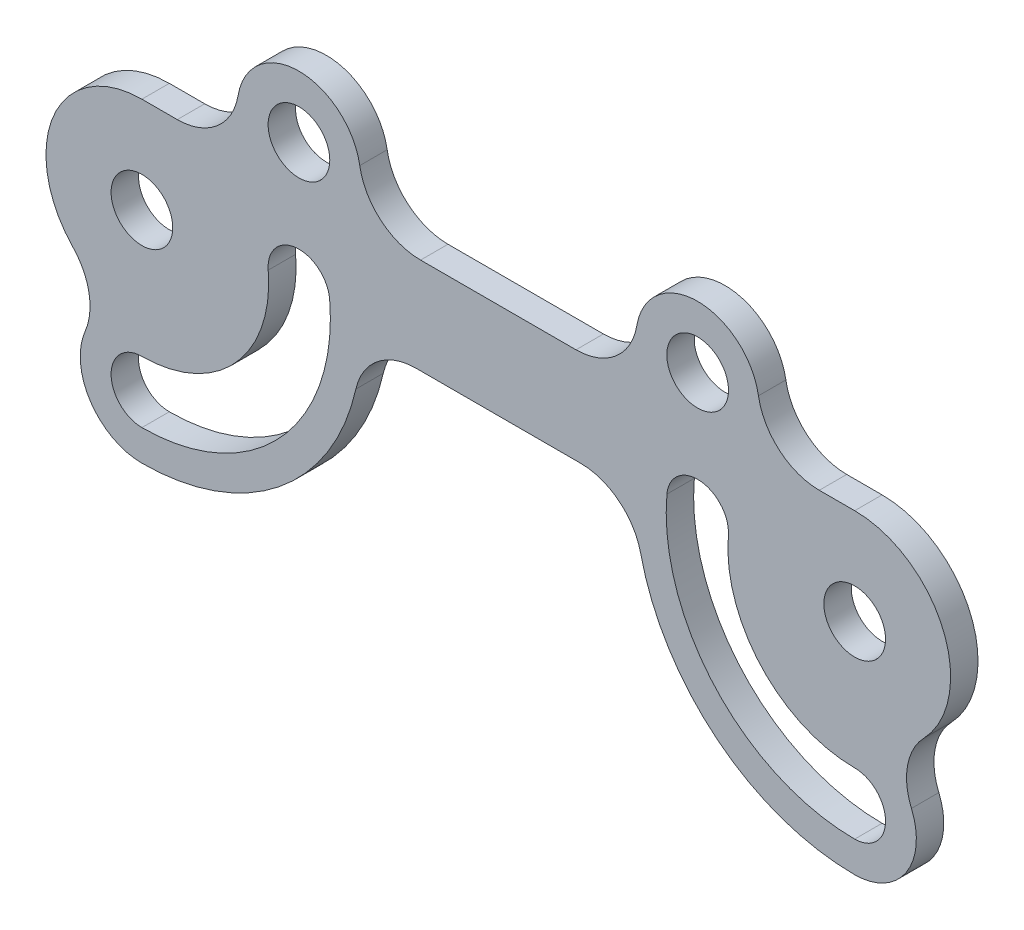
SolidWorks part; units mm, degrees
ref_plane "Front Plane" through (0, 0, 0) normal (0, 0, 1) x (1, 0, 0)
ref_plane "Top Plane" through (0, 0, 0) normal (0, 1, 0) x (1, 0, 0)
ref_plane "Right Plane" through (0, 0, 0) normal (1, 0, 0) x (0, 0, -1)
sketch "Sketch1" plane through (0, 0, 0) normal (0, 0, 1) x (1, 0, 0)
  line L0 (5.5562, 0) -> (35.7188, 0)
  line L1 (0, 5.5562) -> (41.275, 5.5562)
  line L2 (0, 5.5562) -> (0, -5.5562) construction
  line L3 (0, -5.5562) -> (41.275, -5.5562) construction
  line L4 (41.275, 5.5562) -> (41.275, -5.5562) construction
  line L5 (0, 5.5562) -> (41.275, 5.5562) construction
  line L9 (0, 0) -> (9.0934, 0.7956) construction
  line L10 (41.275, 9.1281) -> (41.275, 0) construction
  line L11 (32.1816, 0.7956) -> (30.4025, 0.9512) construction
  line L12 (32.1816, 0.7956) -> (41.275, 0) construction
  line L13 (30.4025, 0.9512) -> (28.6233, 1.1069) construction
  circle A0 centre (0, 0) radius 5.5562 construction
  circle A1 centre (41.275, 0) radius 5.5562 construction
  arc A2 (0, 5.5562) -> (0, -5.5562) centre (0, 0) ccw
  arc A3 (41.275, -5.5562) -> (41.275, 5.5562) centre (41.275, 0) ccw
  circle A4 centre (0, 0) radius 1.7859
  circle A5 centre (41.275, 0) radius 1.7859
  arc A6 (0, -5.5562) -> (5.5562, 0) centre (0, 0) ccw
  arc A7 (35.7188, 0) -> (41.275, -5.5562) centre (41.275, 0) ccw
  circle A16 centre (41.275, -9.1281) radius 1.7859
  circle A20 centre (41.275, -9.1281) radius 3.5719
  circle A21 centre (32.1816, 0.7956) radius 1.7859
  circle A22 centre (32.1816, 0.7956) radius 3.5719 construction
  circle A23 centre (41.275, 0) radius 9.1281 construction
  circle A25 centre (0, 0) radius 9.1281 construction
  circle A40 centre (32.1816, 7.9393) radius 1.7859
  circle A41 centre (32.1816, 7.9393) radius 3.5719
  circle A42 centre (0, -9.1281) radius 3.5719
  circle A46 centre (9.0934, 0.7956) radius 1.7859
  circle A47 centre (9.0934, 7.9393) radius 1.7859
  circle A48 centre (9.0934, 7.9393) radius 3.5719
  circle A49 centre (9.0934, 0.7956) radius 3.5719 construction
  circle A50 centre (0, -9.1281) radius 1.7859
  arc A51 (0, -7.3422) -> (7.3142, 0.6399) centre (0, 0) ccw
  arc A52 (0, -10.9141) -> (10.8725, 0.9512) centre (0, 0) ccw
  arc A53 (0, -12.7) -> (12.6517, 1.1069) centre (0, 0) ccw
  arc A54 (28.6233, 1.1069) -> (41.275, -12.7) centre (41.275, 0) ccw
  arc A55 (30.4025, 0.9512) -> (41.275, -10.9141) centre (41.275, 0) ccw
  arc A56 (33.9608, 0.6399) -> (41.275, -7.3422) centre (41.275, 0) ccw
  dimension "D1" = 41.275
  dimension "D2" = 11.1125
  dimension "D3" = 3.5719
  dimension "D5" = 95
  dimension "D6" = 7.1438
  dimension "D7" = 3.5719
  dimension "D4" = 95
extrude "Boss-Extrude2" add sketch "Sketch1" along normal blind 1.5875
fillet "Fillet2" radius 3.5719 8 edges at (41.275, -5.5562, 0.7937) (0, -5.5563, 0.7937) (12.7, 0, 0.7937) (28.575, 0, 0.7937) (29.5209, 5.5562, 0.7937) (34.8423, 5.5562, 0.7937) (6.4327, 5.5562, 0.7937) (11.7541, 5.5562, 0.7937)
